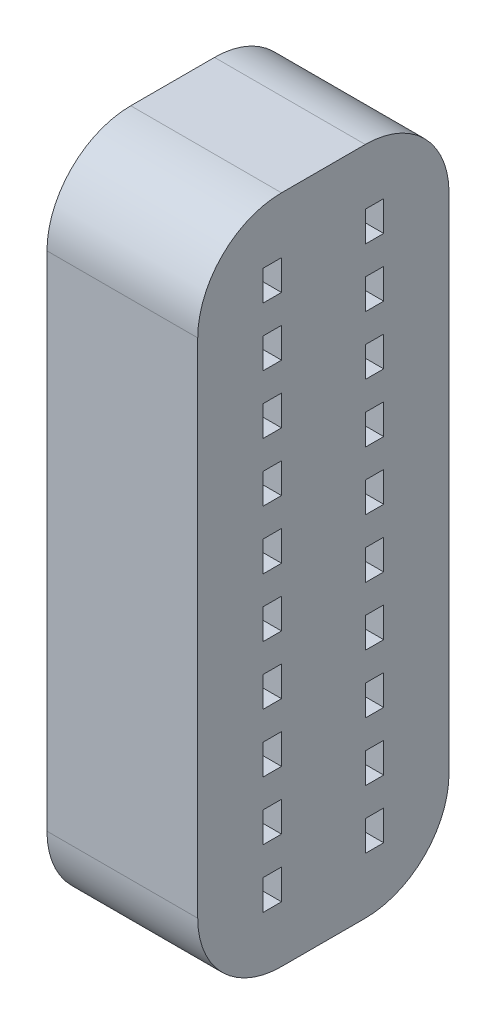
SolidWorks part; units mm, degrees
ref_plane "Front Plane" through (0, 0, 0) normal (1, 0, 0) x (0, 1, 0)
ref_plane "Top Plane" through (0, 0, 0) normal (0, 0, 1) x (0, 1, 0)
ref_plane "Right Plane" through (0, 0, 0) normal (0, 1, 0) x (-1, 0, 0)
sketch "Sketch1" plane through (0, 0, 0) normal (1, 0, 0) x (0, 1, 0)
  line L1 (-15, -7.5) -> (15, -7.5)
  line L2 (-20, -2.5) -> (-20, 2.5)
  line L3 (-15, 7.5) -> (15, 7.5)
  line L4 (20, -2.5) -> (20, 2.5)
  line L5 (-20, -7.5) -> (20, 7.5) construction
  line L6 (-20, 7.5) -> (20, -7.5) construction
  arc A0 (20, -2.5) -> (15, -7.5) centre (15, -2.5) cw
  arc A1 (-15, -7.5) -> (-20, -2.5) centre (-15, -2.5) cw
  arc A2 (20, 2.5) -> (15, 7.5) centre (15, 2.5) ccw
  arc A3 (-15, 7.5) -> (-20, 2.5) centre (-15, 2.5) ccw
  point P0 (0, 0)
  dimension "D3" = 5
  dimension "D1" = 40
  dimension "D2" = 15
extrude "Boss-Extrude1" add sketch "Sketch1" along normal blind 9
sketch "Sketch2" plane through (9, 0, 0) normal (1, 0, 0) x (0, 1, 0)
  line L0 (-11.35, 3.6) -> (-11.35, 2.5)
  line L1 (-16.65, 3.6) -> (-14.85, 3.6)
  line L2 (-16.65, 3.6) -> (-16.65, 2.5)
  line L3 (-16.65, 2.5) -> (-14.85, 2.5)
  line L4 (-14.85, 3.6) -> (-14.85, 2.5)
  line L5 (-13.15, 2.5) -> (-11.35, 2.5)
  line L6 (-13.15, 3.6) -> (-13.15, 2.5)
  line L7 (-13.15, 3.6) -> (-11.35, 3.6)
  line L8 (-7.85, 3.6) -> (-7.85, 2.5)
  line L9 (-9.65, 2.5) -> (-7.85, 2.5)
  line L10 (-9.65, 3.6) -> (-9.65, 2.5)
  line L11 (-9.65, 3.6) -> (-7.85, 3.6)
  line L12 (-4.35, 3.6) -> (-4.35, 2.5)
  line L13 (-6.15, 2.5) -> (-4.35, 2.5)
  line L14 (-6.15, 3.6) -> (-6.15, 2.5)
  line L15 (-6.15, 3.6) -> (-4.35, 3.6)
  line L16 (-0.85, 3.6) -> (-0.85, 2.5)
  line L17 (-2.65, 2.5) -> (-0.85, 2.5)
  line L18 (-2.65, 3.6) -> (-2.65, 2.5)
  line L19 (-2.65, 3.6) -> (-0.85, 3.6)
  line L20 (2.65, 3.6) -> (2.65, 2.5)
  line L21 (0.85, 2.5) -> (2.65, 2.5)
  line L22 (0.85, 3.6) -> (0.85, 2.5)
  line L23 (0.85, 3.6) -> (2.65, 3.6)
  line L24 (6.15, 3.6) -> (6.15, 2.5)
  line L25 (4.35, 2.5) -> (6.15, 2.5)
  line L26 (4.35, 3.6) -> (4.35, 2.5)
  line L27 (4.35, 3.6) -> (6.15, 3.6)
  line L28 (9.65, 3.6) -> (9.65, 2.5)
  line L29 (7.85, 2.5) -> (9.65, 2.5)
  line L30 (7.85, 3.6) -> (7.85, 2.5)
  line L31 (7.85, 3.6) -> (9.65, 3.6)
  line L32 (13.15, 3.6) -> (13.15, 2.5)
  line L33 (11.35, 2.5) -> (13.15, 2.5)
  line L34 (11.35, 3.6) -> (11.35, 2.5)
  line L35 (11.35, 3.6) -> (13.15, 3.6)
  line L36 (16.65, 3.6) -> (16.65, 2.5)
  line L37 (14.85, 2.5) -> (16.65, 2.5)
  line L38 (14.85, 3.6) -> (14.85, 2.5)
  line L39 (14.85, 3.6) -> (16.65, 3.6)
  line L40 (-11.35, -2.5) -> (-11.35, -3.6)
  line L41 (-13.15, -3.6) -> (-11.35, -3.6)
  line L42 (-13.15, -2.5) -> (-13.15, -3.6)
  line L43 (-13.15, -2.5) -> (-11.35, -2.5)
  line L44 (-7.85, -2.5) -> (-7.85, -3.6)
  line L45 (-9.65, -3.6) -> (-7.85, -3.6)
  line L46 (-9.65, -2.5) -> (-9.65, -3.6)
  line L47 (-9.65, -2.5) -> (-7.85, -2.5)
  line L48 (-4.35, -2.5) -> (-4.35, -3.6)
  line L49 (-6.15, -3.6) -> (-4.35, -3.6)
  line L50 (-6.15, -2.5) -> (-6.15, -3.6)
  line L51 (-6.15, -2.5) -> (-4.35, -2.5)
  line L52 (-0.85, -2.5) -> (-0.85, -3.6)
  line L53 (-2.65, -3.6) -> (-0.85, -3.6)
  line L54 (-2.65, -2.5) -> (-2.65, -3.6)
  line L55 (-2.65, -2.5) -> (-0.85, -2.5)
  line L56 (2.65, -2.5) -> (2.65, -3.6)
  line L57 (0.85, -3.6) -> (2.65, -3.6)
  line L58 (0.85, -2.5) -> (0.85, -3.6)
  line L59 (0.85, -2.5) -> (2.65, -2.5)
  line L60 (6.15, -2.5) -> (6.15, -3.6)
  line L61 (4.35, -3.6) -> (6.15, -3.6)
  line L62 (4.35, -2.5) -> (4.35, -3.6)
  line L63 (4.35, -2.5) -> (6.15, -2.5)
  line L64 (9.65, -2.5) -> (9.65, -3.6)
  line L65 (7.85, -3.6) -> (9.65, -3.6)
  line L66 (7.85, -2.5) -> (7.85, -3.6)
  line L67 (7.85, -2.5) -> (9.65, -2.5)
  line L68 (13.15, -2.5) -> (13.15, -3.6)
  line L69 (11.35, -3.6) -> (13.15, -3.6)
  line L70 (11.35, -2.5) -> (11.35, -3.6)
  line L71 (11.35, -2.5) -> (13.15, -2.5)
  line L72 (16.65, -2.5) -> (16.65, -3.6)
  line L73 (14.85, -3.6) -> (16.65, -3.6)
  line L74 (14.85, -2.5) -> (14.85, -3.6)
  line L75 (14.85, -2.5) -> (16.65, -2.5)
  line L76 (-14.85, -2.5) -> (-14.85, -3.6)
  line L77 (-16.65, -3.6) -> (-14.85, -3.6)
  line L78 (-16.65, -2.5) -> (-16.65, -3.6)
  line L79 (-16.65, -2.5) -> (-14.85, -2.5)
  line L80 (0, 7.5) -> (0, -7.5) construction
  line L81 (15, 7.5) -> (-15, 7.5) construction
  line L82 (-15, -7.5) -> (15, -7.5) construction
  line L83 (-15.75, 2.5) -> (-15.75, -2.5) construction
  line L84 (15.75, 2.5) -> (15.75, -2.5) construction
  line L85 (-15.75, 0) -> (15.75, 0) construction
  line L86 (-15.75, 3.6) -> (-15.75, 2.5) construction
  line L87 (-12.25, 3.6) -> (-12.25, 2.5) construction
  line L88 (-15.75, -2.5) -> (-15.75, -3.6) construction
  line L89 (-12.25, -2.5) -> (-12.25, -3.6) construction
  line L90 (-12.25, -3.05) -> (-15.75, -3.05) construction
  line L91 (-12.25, 3.05) -> (-15.75, 3.05) construction
  dimension "D1" = 1.8
  dimension "D2" = 1.1
  dimension "D5" = 3.5
  dimension "D6" = 6.1
  dimension "D3" = 10
  dimension "D4" = 2
extrude "Cut-Extrude1" cut sketch "Sketch2" against normal through all
sketch "Sketch3" plane through (0, 0, 0) normal (-1, 0, 0) x (0, -1, 0)
  line L0 (-16.65, 2.5) -> (-14.85, 2.5)
  line L1 (-14.85, 2.5) -> (-14.85, 1.4)
  line L2 (-14.85, 1.4) -> (-16.65, 1.4)
  line L3 (-16.65, 1.4) -> (-16.65, 2.5)
  line L4 (-16.65, 2.5) -> (-16.65, 3.6) construction
  line L5 (-13.15, 2.5) -> (-11.35, 2.5)
  line L6 (-11.35, 2.5) -> (-11.35, 1.4)
  line L7 (-11.35, 1.4) -> (-13.15, 1.4)
  line L8 (-13.15, 1.4) -> (-13.15, 2.5)
  line L9 (-9.65, 2.5) -> (-7.85, 2.5)
  line L10 (-7.85, 2.5) -> (-7.85, 1.4)
  line L11 (-7.85, 1.4) -> (-9.65, 1.4)
  line L12 (-9.65, 1.4) -> (-9.65, 2.5)
  line L13 (-6.15, 2.5) -> (-4.35, 2.5)
  line L14 (-4.35, 2.5) -> (-4.35, 1.4)
  line L15 (-4.35, 1.4) -> (-6.15, 1.4)
  line L16 (-6.15, 1.4) -> (-6.15, 2.5)
  line L17 (-2.65, 2.5) -> (-0.85, 2.5)
  line L18 (-0.85, 2.5) -> (-0.85, 1.4)
  line L19 (-0.85, 1.4) -> (-2.65, 1.4)
  line L20 (-2.65, 1.4) -> (-2.65, 2.5)
  line L21 (0.85, 2.5) -> (2.65, 2.5)
  line L22 (2.65, 2.5) -> (2.65, 1.4)
  line L23 (2.65, 1.4) -> (0.85, 1.4)
  line L24 (0.85, 1.4) -> (0.85, 2.5)
  line L25 (4.35, 2.5) -> (6.15, 2.5)
  line L26 (6.15, 2.5) -> (6.15, 1.4)
  line L27 (6.15, 1.4) -> (4.35, 1.4)
  line L28 (4.35, 1.4) -> (4.35, 2.5)
  line L29 (7.85, 2.5) -> (9.65, 2.5)
  line L30 (9.65, 2.5) -> (9.65, 1.4)
  line L31 (9.65, 1.4) -> (7.85, 1.4)
  line L32 (7.85, 1.4) -> (7.85, 2.5)
  line L33 (11.35, 2.5) -> (13.15, 2.5)
  line L34 (13.15, 2.5) -> (13.15, 1.4)
  line L35 (13.15, 1.4) -> (11.35, 1.4)
  line L36 (11.35, 1.4) -> (11.35, 2.5)
  line L37 (14.85, 2.5) -> (16.65, 2.5)
  line L38 (16.65, 2.5) -> (16.65, 1.4)
  line L39 (16.65, 1.4) -> (14.85, 1.4)
  line L40 (14.85, 1.4) -> (14.85, 2.5)
  line L41 (-16.65, -3.6) -> (-14.85, -3.6)
  line L42 (-14.85, -3.6) -> (-14.85, -4.7)
  line L43 (-14.85, -4.7) -> (-16.65, -4.7)
  line L44 (-16.65, -4.7) -> (-16.65, -3.6)
  line L45 (-16.65, -3.6) -> (-16.65, -2.5) construction
  line L46 (-13.15, -3.6) -> (-11.35, -3.6)
  line L47 (-11.35, -3.6) -> (-11.35, -4.7)
  line L48 (-11.35, -4.7) -> (-13.15, -4.7)
  line L49 (-13.15, -4.7) -> (-13.15, -3.6)
  line L50 (-9.65, -3.6) -> (-7.85, -3.6)
  line L51 (-7.85, -3.6) -> (-7.85, -4.7)
  line L52 (-7.85, -4.7) -> (-9.65, -4.7)
  line L53 (-9.65, -4.7) -> (-9.65, -3.6)
  line L54 (-6.15, -3.6) -> (-4.35, -3.6)
  line L55 (-4.35, -3.6) -> (-4.35, -4.7)
  line L56 (-4.35, -4.7) -> (-6.15, -4.7)
  line L57 (-6.15, -4.7) -> (-6.15, -3.6)
  line L58 (-2.65, -3.6) -> (-0.85, -3.6)
  line L59 (-0.85, -3.6) -> (-0.85, -4.7)
  line L60 (-0.85, -4.7) -> (-2.65, -4.7)
  line L61 (-2.65, -4.7) -> (-2.65, -3.6)
  line L62 (0.85, -3.6) -> (2.65, -3.6)
  line L63 (2.65, -3.6) -> (2.65, -4.7)
  line L64 (2.65, -4.7) -> (0.85, -4.7)
  line L65 (0.85, -4.7) -> (0.85, -3.6)
  line L66 (4.35, -3.6) -> (6.15, -3.6)
  line L67 (6.15, -3.6) -> (6.15, -4.7)
  line L68 (6.15, -4.7) -> (4.35, -4.7)
  line L69 (4.35, -4.7) -> (4.35, -3.6)
  line L70 (7.85, -3.6) -> (9.65, -3.6)
  line L71 (9.65, -3.6) -> (9.65, -4.7)
  line L72 (9.65, -4.7) -> (7.85, -4.7)
  line L73 (7.85, -4.7) -> (7.85, -3.6)
  line L74 (11.35, -3.6) -> (13.15, -3.6)
  line L75 (13.15, -3.6) -> (13.15, -4.7)
  line L76 (13.15, -4.7) -> (11.35, -4.7)
  line L77 (11.35, -4.7) -> (11.35, -3.6)
  line L78 (14.85, -3.6) -> (16.65, -3.6)
  line L79 (16.65, -3.6) -> (16.65, -4.7)
  line L80 (16.65, -4.7) -> (14.85, -4.7)
  line L81 (14.85, -4.7) -> (14.85, -3.6)
  point P8 (-15.75, 1.4)
  point P9 (-12.25, 1.4)
  point P54 (-15.75, -4.7)
  point P91 (-12.25, -4.7)
  dimension "D2" = 3.5
  dimension "D4" = 3.5
  dimension "D1" = 10
  dimension "D3" = 10
extrude "Cut-Extrude2" cut sketch "Sketch3" against normal offset from surface (7 mm away) 2 up to face at (9, -5.25, -3.05)
